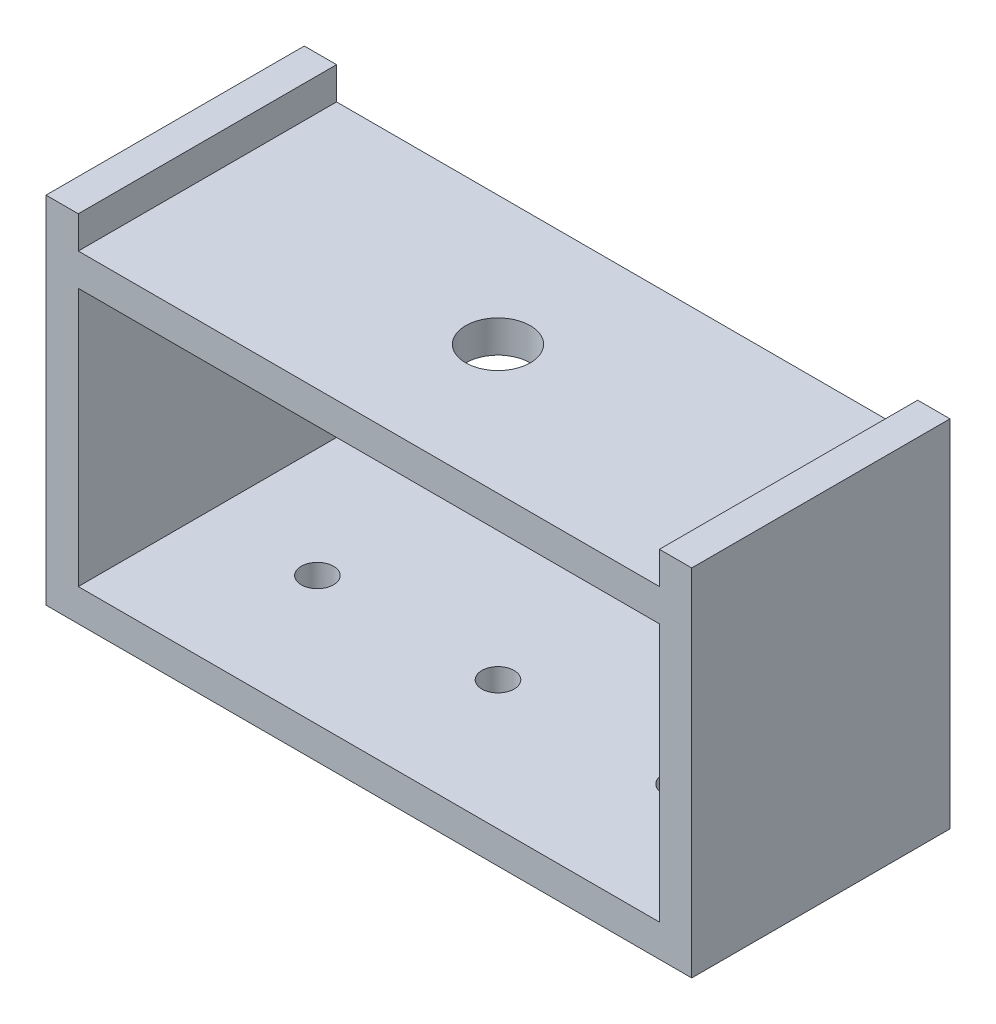
SolidWorks part; units mm, degrees
material "ABS"
ref_plane "Front Plane" through (0, 0, 0) normal (0, 0, 1) x (1, 0, 0)
ref_plane "Top Plane" through (0, 0, 0) normal (0, 1, 0) x (1, 0, 0)
ref_plane "Right Plane" through (0, 0, 0) normal (1, 0, 0) x (0, 0, -1)
sketch "Sketch1" plane through (0, 0, 0) normal (1, 0, 0) x (0, 0, -1)
  line L1 (-25.4, -31.75) -> (25.4, -31.75)
  line L2 (-25.4, -31.75) -> (-25.4, 31.75)
  line L3 (-25.4, 31.75) -> (25.4, 31.75)
  line L4 (25.4, -31.75) -> (25.4, 31.75)
  line L5 (-25.4, -31.75) -> (25.4, 31.75) construction
  line L6 (-25.4, 31.75) -> (25.4, -31.75) construction
  point P0 (0, 0)
  dimension "D1" = 50.8
  dimension "D2" = 63.5
extrude "Boss-Extrude1" add sketch "Sketch1" along normal blind 127
sketch "Sketch2" plane through (0, 31.75, 0) normal (0, 1, 0) x (1, 0, 0)
  line L0 (63.5, 25.4) -> (63.5, -25.4) construction
  line L1 (127, 25.4) -> (0, 25.4) construction
  line L2 (127, -25.4) -> (0, -25.4) construction
  line L3 (127, -25.4) -> (120.65, -25.4)
  line L4 (0, 25.4) -> (6.35, 25.4)
  line L5 (0, 25.4) -> (0, -25.4)
  line L6 (0, -25.4) -> (6.35, -25.4)
  line L7 (6.35, 25.4) -> (6.35, -25.4)
  line L8 (127, 25.4) -> (127, -25.4)
  line L9 (127, 25.4) -> (120.65, 25.4)
  line L10 (120.65, 25.4) -> (120.65, -25.4)
  dimension "D1" = 6.35
extrude "Boss-Extrude2" add sketch "Sketch2" along normal blind 6.35
sketch "Sketch4" plane through (0, 0, 0) normal (0, 0, 1) x (1, 0, 0)
  line L0 (6.35, 25.4) -> (6.35, -25.4)
  line L1 (6.35, -25.4) -> (120.65, -25.4)
  line L2 (120.65, -25.4) -> (120.65, 25.4)
  line L3 (120.65, 25.4) -> (120.65, 25.4)
  line L4 (120.65, 25.4) -> (120.65, 25.4)
  line L5 (120.65, 25.4) -> (6.35, 25.4)
  line L6 (6.35, 25.4) -> (6.35, 25.4)
  line L7 (6.35, 25.4) -> (6.35, 25.4)
  line L8 (0, 38.1) -> (0, -31.75)
  line L9 (0, -31.75) -> (127, -31.75)
  line L10 (127, -31.75) -> (127, 38.1)
  line L11 (127, 38.1) -> (120.65, 38.1)
  line L12 (120.65, 38.1) -> (120.65, 31.75)
  line L13 (120.65, 31.75) -> (6.35, 31.75)
  line L14 (6.35, 31.75) -> (6.35, 38.1)
  line L15 (6.35, 38.1) -> (0, 38.1)
  line L16 (0, 38.1) -> (0, -31.75) construction
  line L17 (0, -31.75) -> (127, -31.75) construction
  line L18 (127, -31.75) -> (127, 38.1) construction
  line L19 (127, 38.1) -> (120.65, 38.1) construction
  line L20 (120.65, 38.1) -> (120.65, 31.75) construction
  line L21 (120.65, 31.75) -> (6.35, 31.75) construction
  line L22 (6.35, 31.75) -> (6.35, 38.1) construction
  line L23 (6.35, 38.1) -> (0, 38.1) construction
  dimension "D1" = 0
  dimension "D2" = 6.35
extrude "Cut-Extrude2" cut sketch "Sketch4" against normal through all both and the other way through all
sketch "Sketch5" plane through (0, 31.75, 0) normal (0, 1, 0) x (1, 0, 0)
  line L0 (0, 0) -> (127, 0) construction
  line L1 (127, -25.4) -> (127, 25.4) construction
  circle A0 centre (63.5, 0) radius 6.35
  dimension "D1" = 12.7
extrude "Cut-Extrude3" cut sketch "Sketch5" against normal up to next
sketch "Sketch6" plane through (0, -25.4, 0) normal (0, 1, 0) x (1, 0, 0)
  line L0 (0, 0) -> (127, 0) construction
  line L1 (127, -25.4) -> (127, 25.4) construction
  line L2 (63.5, -25.4) -> (63.5, 25.4) construction
  line L3 (120.65, 25.4) -> (6.35, 25.4) construction
  circle A0 centre (63.5, 0) radius 3.175
  circle A1 centre (27.9834, 0) radius 3.175
  circle A2 centre (99.0166, 0) radius 3.175
  point P5 (63.5, 0)
  point P13 (63.5, 0)
  point P16 (0, 0)
  dimension "D1" = 6.35
  dimension "D2" = 6.35
  dimension "D3" = 35.5166
extrude "Cut-Extrude4" cut sketch "Sketch6" against normal up to next
